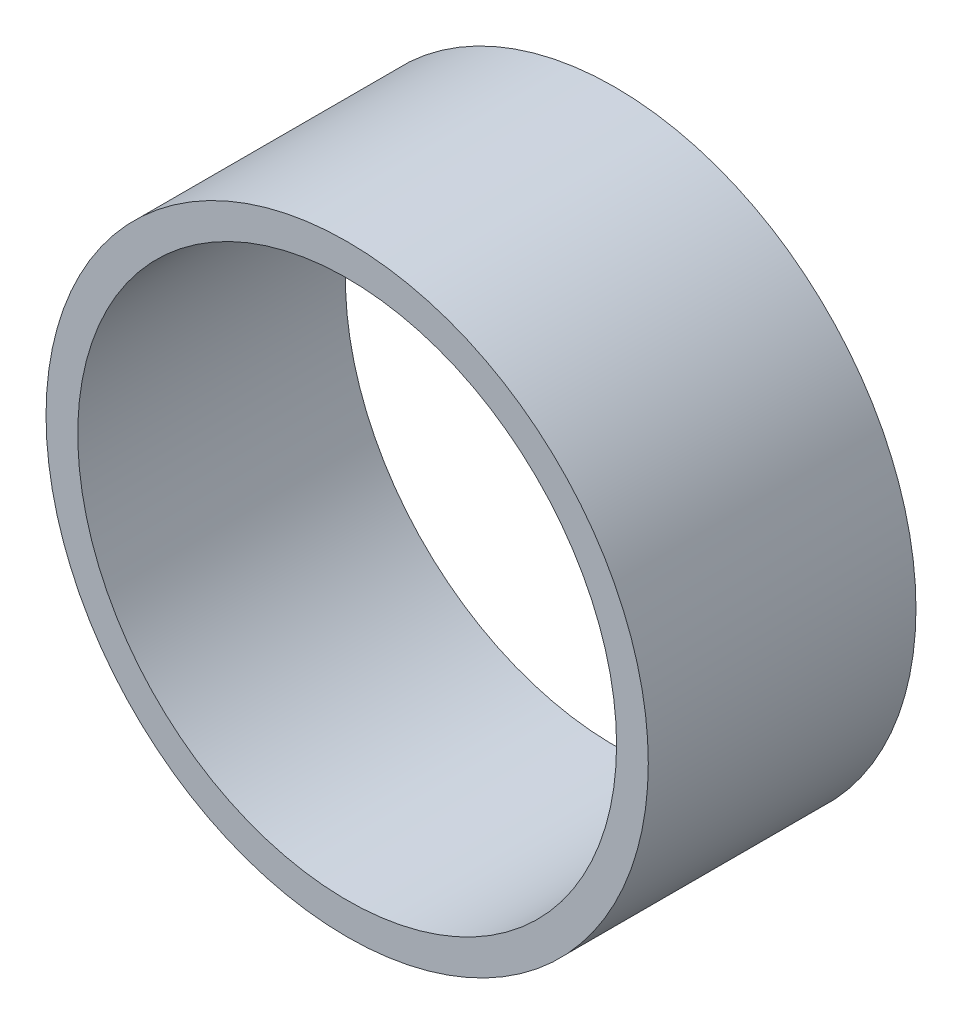
SolidWorks part; units mm, degrees
ref_plane "Front" through (0, 0, 0) normal (0, 0, 1) x (1, 0, 0)
ref_plane "Top" through (0, 0, 0) normal (0, 1, 0) x (1, 0, 0)
ref_plane "Side" through (0, 0, 0) normal (1, 0, 0) x (0, 0, -1)
other "Configuration Table"
sketch "PipeSketch" plane through (0, 0, 0) normal (0, 0, 1) x (1, 0, 0)
  circle A0 centre (0, 0) radius 57.15
  circle A1 centre (0, 0) radius 51.1302
  dimension "OuterDiameter" = 114.3
  dimension "InnerDiameter" = 102.2604
extrude "Extrusion" add sketch "PipeSketch" along normal blind 50.8
sketch "FilterSketch" plane through (0, 0, 0) normal (0, 0, 1) x (1, 0, 0)
  circle A0 centre (0, 0) radius 50.8 construction
  dimension "NominalDiameter" = 101.6
